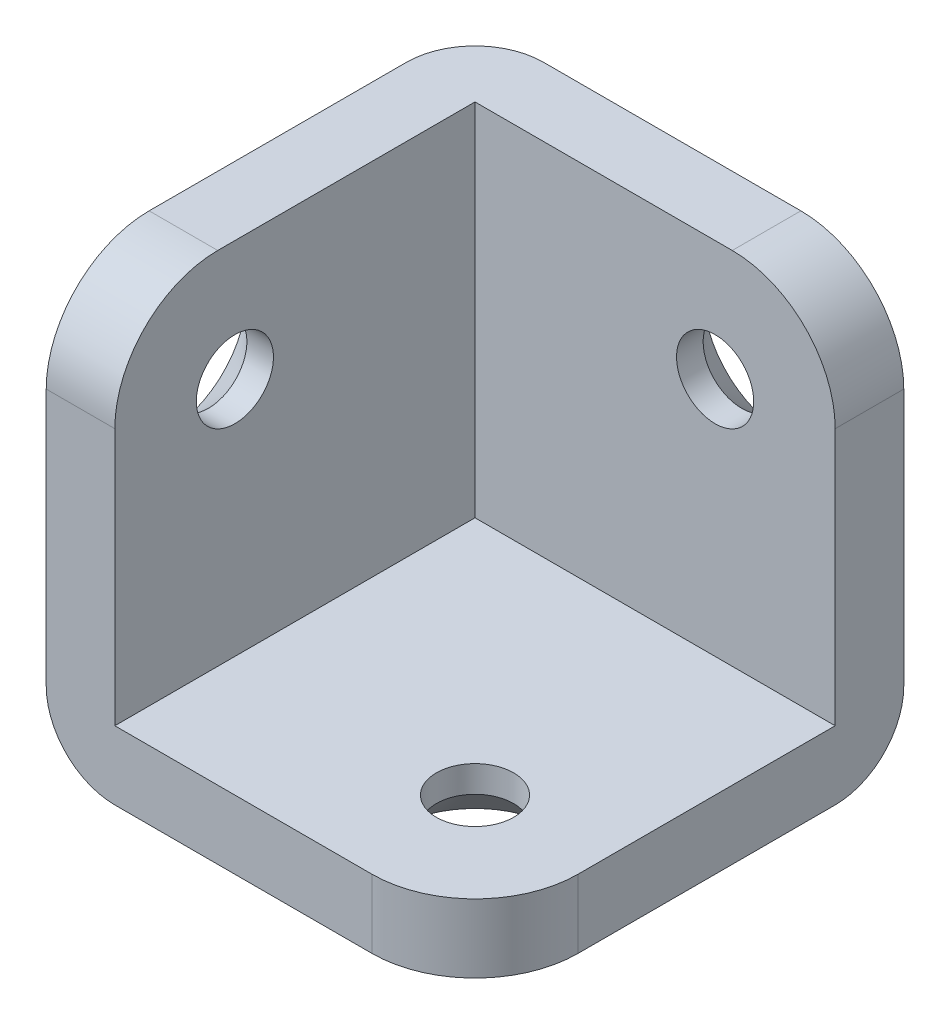
SolidWorks part; units mm, degrees
ref_plane "Front Plane" through (0, 0, 0) normal (0, 0, 1) x (1, 0, 0)
ref_plane "Top Plane" through (0, 0, 0) normal (0, 1, 0) x (1, 0, 0)
ref_plane "Right Plane" through (0, 0, 0) normal (1, 0, 0) x (0, 0, -1)
sketch "Sketch1" plane through (0, 0, 0) normal (0, 1, 0) x (1, 0, 0)
  line L1 (0, 0) -> (25, 0)
  line L2 (0, 0) -> (0, -25)
  line L3 (0, -25) -> (25, -25)
  line L4 (25, 0) -> (25, -25)
  dimension "D1" = 25
  dimension "D2" = 25
extrude "Boss-Extrude1" add sketch "Sketch1" along normal blind 25
sketch "Sketch2" plane through (0, 25, 0) normal (0, 1, 0) x (1, 0, 0)
  line L0 (0, 0) -> (0, -25) construction
  line L1 (25, -25) -> (4, -25)
  line L2 (25, -25) -> (25, -4)
  line L3 (25, -4) -> (4, -4)
  line L4 (4, -25) -> (4, -4)
  line L5 (25, 0) -> (0, 0) construction
  dimension "D1" = 4
  dimension "D2" = 4
extrude "Cut-Extrude1" cut sketch "Sketch2" against normal offset from surface (21 mm away) 4 up to face at (12.5, 0, 12.5)
fillet "Fillet1" radius 6 3 edges at (25, 2, 25) (25, 25, 2) (2, 25, 25)
hole_wizard "CSK for M4 Countersunk Flat Head Screw2" positions "3DSketch2" profile "Sketch4" countersink size "M4" standard "ISO" end condition up to next
sketch3d "3DSketch2"
  line L0 (0, 0, 0) -> (0, 0, 25) construction
  line L1 (25, 0, 0) -> (0, 0, 0) construction
  line L2 (0, 25, 0) -> (0, 0, 0) construction
  point P0 (18, 18, 0)
  point P2 (0, 18, 18)
  point P4 (18, 0, 18)
  point P9 (0, 0, 0)
  dimension "D1" = 18
  dimension "D2" = 18
  dimension "D3" = 18
  dimension "D4" = 18
  dimension "D5" = 18
  dimension "D6" = 18
sketch "Sketch4" plane through (18, 18, 0) normal (1, 0, 0) x (0, 1, 0)
  line L0 (0, 0) -> (0, 4)
  line L1 (0, 4) -> (2.25, 4)
  line L2 (2.25, 4) -> (2.25, 2.45)
  line L3 (2.25, 2.45) -> (4.7, 0)
  line L5 (4.7, 0) -> (0, 0)
  line L6 (-2.25, 2.45) -> (-4.7, 0) construction
  line L11 (0, -6.35) -> (0, 107.95) construction
  dimension "Thru Hole Dia." = 4.5
  dimension "Thru Hole Depth" = 4
  dimension "Near C'Sink Dia." = 9.4
  dimension "Near C'Sink Angle" = 90
fillet "Fillet2" radius 4 3 edges at (0, 0, 12.5) (0, 12.5, 0) (12.5, 0, 0)
equation "\"wall_thickness\"=25.0076"
